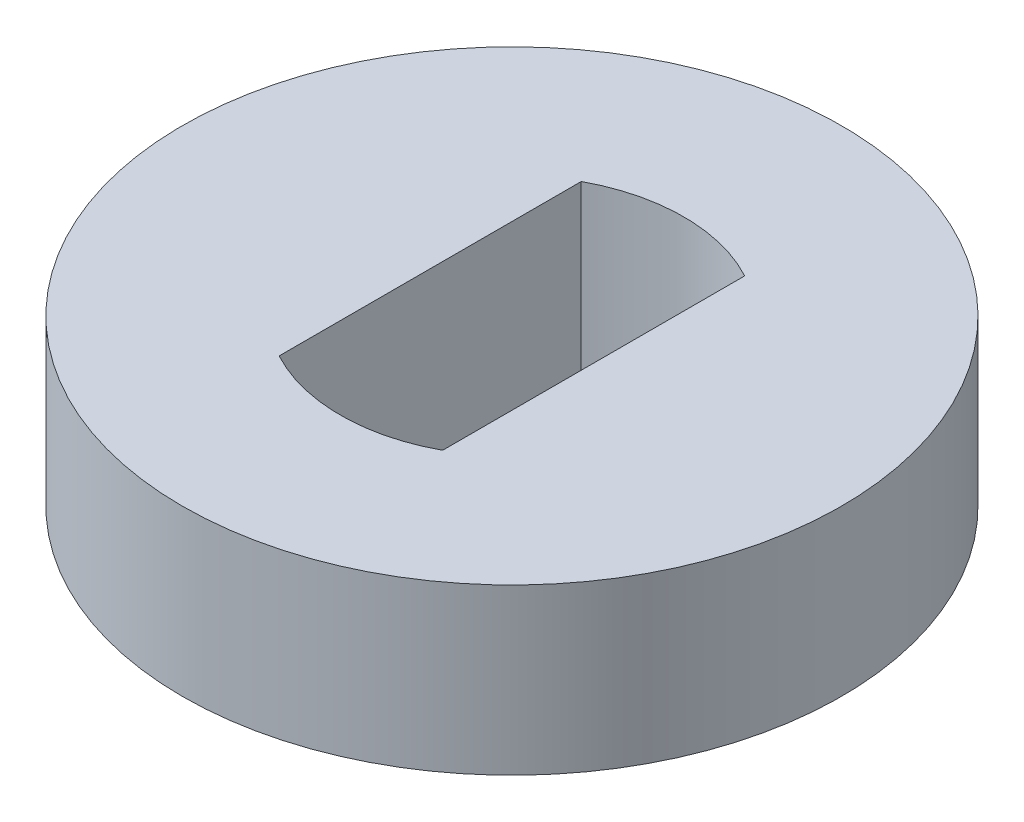
SolidWorks part; units mm, degrees
ref_plane "Front Plane" through (0, 0, 0) normal (0, 0, 1) x (1, 0, 0)
ref_plane "Top Plane" through (0, 0, 0) normal (0, 1, 0) x (1, 0, 0)
ref_plane "Right Plane" through (0, 0, 0) normal (1, 0, 0) x (0, 0, -1)
sketch "Sketch1" plane through (0, 0, 0) normal (0, 1, 0) x (1, 0, 0)
  line L8 (-1.4882, -2.75) -> (-1.4882, 2.75)
  line L10 (1.4882, -2.75) -> (1.4882, 2.75)
  line L11 (-1.4882, -2.75) -> (1.4882, 2.75) construction
  line L12 (-1.4882, 2.75) -> (1.4882, -2.75) construction
  circle A0 centre (0, 0) radius 6
  arc A5 (-1.4882, -2.75) -> (1.4882, -2.75) centre (0, 0) ccw
  arc A6 (1.4882, 2.75) -> (-1.4882, 2.75) centre (0, 0) ccw
  dimension "D1" = 12
  dimension "D2" = 5.5
  dimension "D3" = 2.9763
extrude "Boss-Extrude1" add sketch "Sketch1" along normal blind 3
